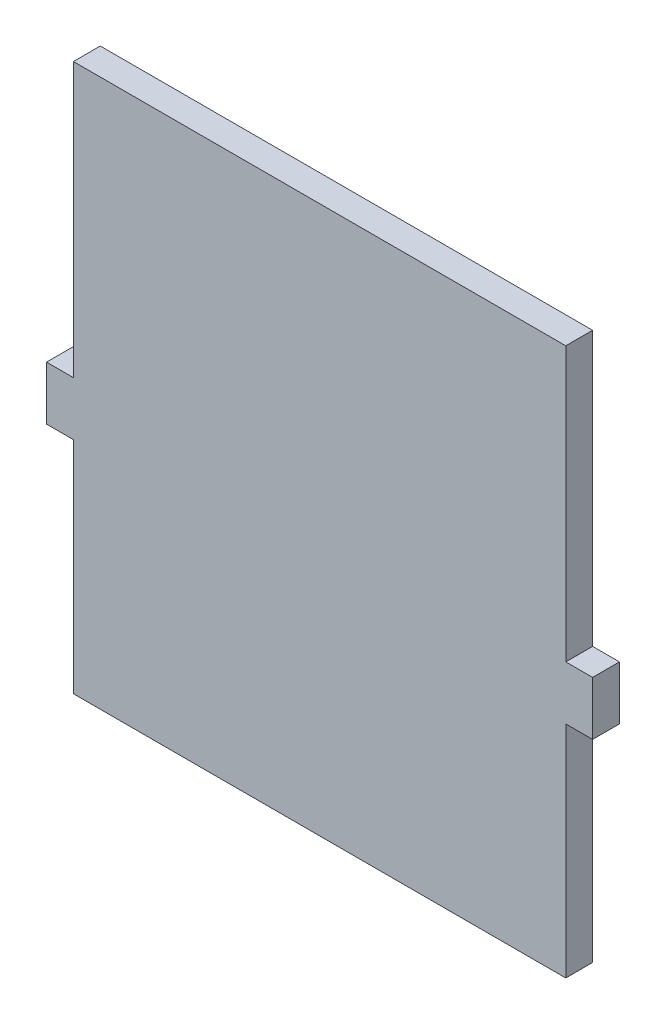
SolidWorks part; units mm, degrees
ref_plane "Přední rovina" through (0, 0, 0) normal (0, 0, 1) x (1, 0, 0)
ref_plane "Horní rovina" through (0, 0, 0) normal (0, 1, 0) x (1, 0, 0)
ref_plane "Pravá rovina" through (0, 0, 0) normal (1, 0, 0) x (0, 0, -1)
sketch "Skica1" plane through (0, 0, 0) normal (0, 0, 1) x (1, 0, 0)
  line L0 (55, -36.58) -> (55, -61.16)
  line L1 (0, 0) -> (55, 0)
  line L2 (0, 0) -> (0, -30.58)
  line L3 (0, -61.16) -> (55, -61.16)
  line L4 (55, 0) -> (55, -30.58)
  line L5 (0, -30.58) -> (-3, -30.58)
  line L6 (0, -36.58) -> (-3, -36.58)
  line L7 (-3, -30.58) -> (-3, -36.58)
  line L8 (55, -30.58) -> (58, -30.58)
  line L9 (55, -36.58) -> (58, -36.58)
  line L10 (58, -30.58) -> (58, -36.58)
  line L11 (0, -36.58) -> (0, -61.16)
  dimension "D1" = 55
  dimension "D2" = 61.16
  dimension "D3" = 30.58
  dimension "D4" = 0
  dimension "D5" = 6
  dimension "D6" = 6
  dimension "D7" = 3
  dimension "D8" = 3
  dimension "D9" = 30.58
extrude "Přidat vysunutím1" add sketch "Skica1" along normal blind 3
